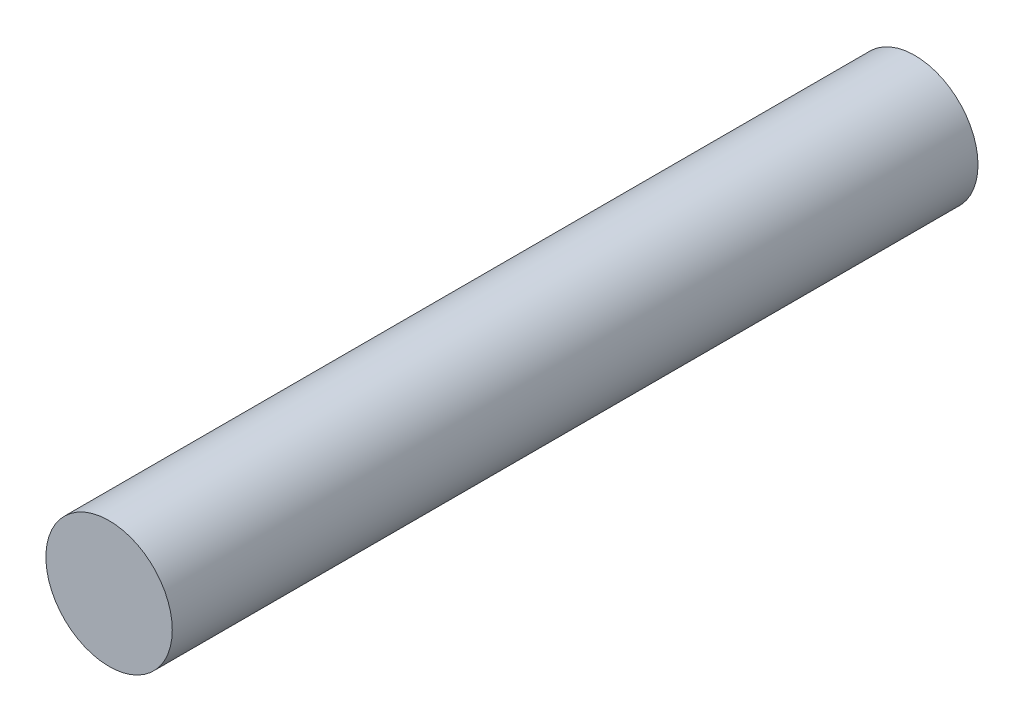
SolidWorks part; units mm, degrees
ref_plane "Front Plane" through (0, 0, 0) normal (0, 0, 1) x (1, 0, 0)
ref_plane "Top Plane" through (0, 0, 0) normal (0, 1, 0) x (1, 0, 0)
ref_plane "Right Plane" through (0, 0, 0) normal (1, 0, 0) x (0, 0, -1)
sketch "Sketch1" plane through (0, 0, 0) normal (0, 0, 1) x (1, 0, 0)
  circle A0 centre (0, 0) radius 4
extrude "Boss-Extrude1" add sketch "Sketch1" along normal blind 51
